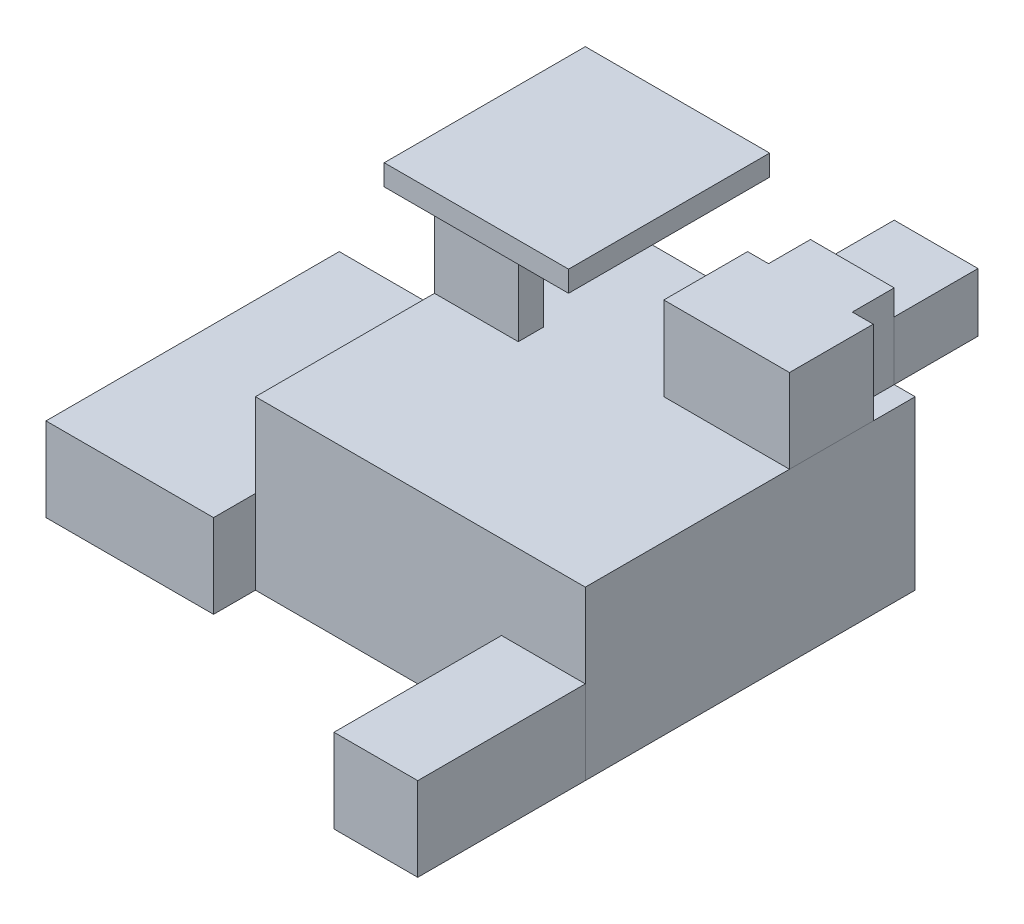
SolidWorks part; units mm, degrees
ref_plane "Front Plane" through (0, 0, 0) normal (0, 0, 1) x (1, 0, 0)
ref_plane "Top Plane" through (0, 0, 0) normal (0, 1, 0) x (1, 0, 0)
ref_plane "Right Plane" through (0, 0, 0) normal (1, 0, 0) x (0, 0, -1)
sketch "Sketch1" plane through (0, 0, 0) normal (0, 1, 0) x (1, 0, 0)
  line L1 (0, 0) -> (50, 0)
  line L2 (0, 0) -> (0, 50)
  line L3 (0, 50) -> (50, 50)
  line L4 (50, 0) -> (50, 50)
extrude "main boards" add sketch "Sketch1" along normal blind 25.4
sketch "Sketch2" plane through (0, 0, 0) normal (0, 0, 1) x (1, 0, 0)
  line L1 (50, 0) -> (37.3, 0)
  line L2 (50, 0) -> (50, 12.7)
  line L3 (50, 12.7) -> (37.3, 12.7)
  line L4 (37.3, 0) -> (37.3, 12.7)
extrude "USB" add sketch "Sketch2" along normal blind 25.4 separate body
sketch "Sketch3" plane through (0, 0, 0) normal (-1, 0, 0) x (0, 0, 1)
  line L0 (0, 25.4) -> (0, 0) construction
  line L1 (6.35, 0) -> (-38.1, 0)
  line L2 (6.35, 0) -> (6.35, 12.7)
  line L3 (6.35, 12.7) -> (-38.1, 12.7)
  line L4 (-38.1, 0) -> (-38.1, 12.7)
  dimension "D1" = 6.35
  dimension "D2" = 38.1
  dimension "D3" = 12.7
extrude "PICKIT" add sketch "Sketch3" along normal blind 25.4 separate body
sketch "Sketch4" plane through (0, 25.4, 0) normal (0, 1, 0) x (1, 0, 0)
  line L0 (50, 0) -> (50, 50) construction
  line L1 (50, 43.65) -> (46.825, 43.65)
  line L2 (50, 43.65) -> (50, 30.95)
  line L3 (50, 30.95) -> (30.95, 30.95)
  line L4 (30.95, 43.65) -> (30.95, 30.95)
  line L5 (50, 50) -> (0, 50) construction
  line L6 (34.125, 43.65) -> (30.95, 43.65)
  line L8 (46.825, 43.65) -> (46.825, 50)
  line L9 (46.825, 50) -> (34.125, 50)
  line L10 (34.125, 43.65) -> (34.125, 50)
  dimension "D1" = 6.35
  dimension "D2" = 12.7
  dimension "D3" = 19.05
  dimension "D4" = 3.175
  dimension "D5" = 12.7
extrude "hbridge" add sketch "Sketch4" along normal blind 12.7 separate body
sketch "Sketch5" plane through (0, 25.4, 0) normal (0, 1, 0) x (1, 0, 0)
  line L1 (46.825, 50) -> (34.125, 50)
  line L2 (46.825, 50) -> (46.825, 62.7)
  line L3 (46.825, 62.7) -> (34.125, 62.7)
  line L4 (34.125, 50) -> (34.125, 62.7)
  line L5 (50, 0) -> (50, 50) construction
  line L6 (46.825, 50) -> (34.125, 50) construction
  dimension "D1" = 3.175
  dimension "D2" = 12.7
  dimension "D3" = 12.7
extrude "motor wiring" add sketch "Sketch5" along normal blind 8.89 separate body
sketch "Sketch6" plane through (0, 25.4, 0) normal (0, 1, 0) x (1, 0, 0)
  line L0 (0, 50) -> (0, 0) construction
  line L1 (12.7, 30.95) -> (0, 30.95)
  line L2 (12.7, 30.95) -> (12.7, 27.14)
  line L3 (12.7, 27.14) -> (0, 27.14)
  line L4 (0, 30.95) -> (0, 27.14)
  line L5 (30.95, 30.95) -> (50, 30.95) construction
  dimension "D1" = 12.7
  dimension "D2" = 3.81
extrude "header" add sketch "Sketch6" along normal blind 11.43 separate body
sketch "Sketch7" plane through (0, 36.83, 0) normal (0, 1, 0) x (1, 0, 0)
  line L0 (0, 50) -> (0, 0) construction
  line L1 (21.59, 25.87) -> (-6.35, 25.87)
  line L2 (21.59, 25.87) -> (21.59, 56.35)
  line L3 (21.59, 56.35) -> (-6.35, 56.35)
  line L4 (-6.35, 25.87) -> (-6.35, 56.35)
  line L5 (0, 27.14) -> (12.7, 27.14) construction
  line L6 (50, 50) -> (0, 50) construction
  dimension "D1" = 6.35
  dimension "D2" = 27.94
  dimension "D3" = 1.27
  dimension "D4" = 6.35
extrude "OLED" add sketch "Sketch7" along normal blind 3.175 separate body
ref_plane "centerline" through (25, 0, 0) normal (1, 0, 0) x (0, 0, -1)
